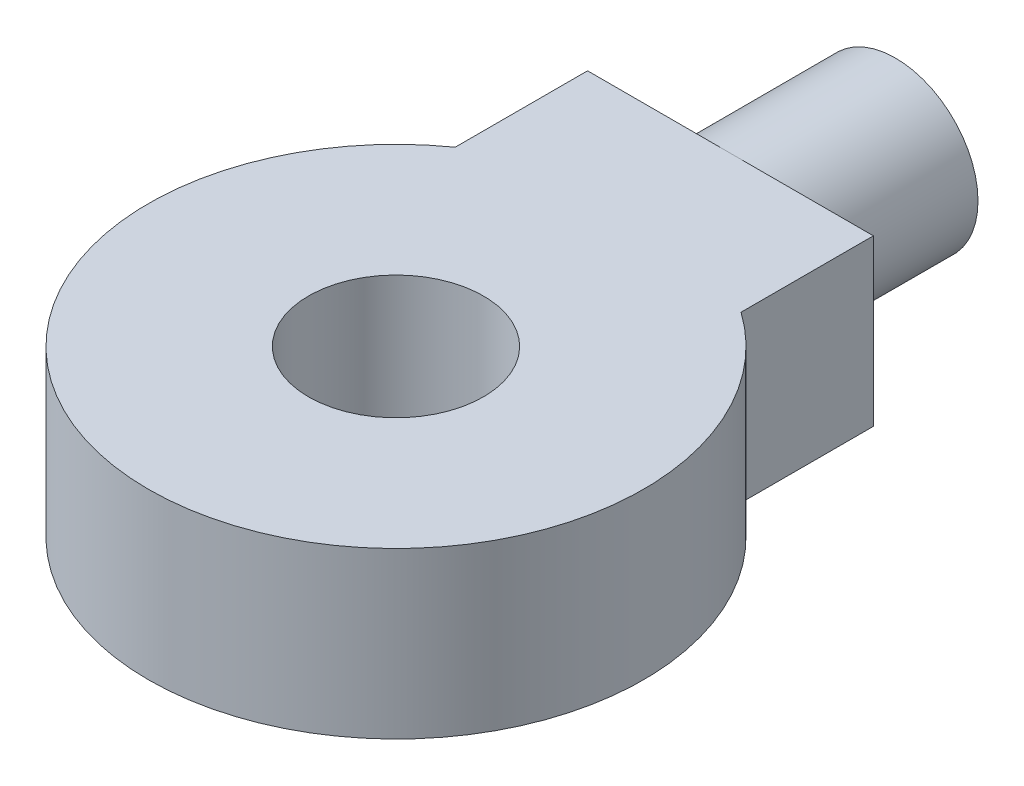
SolidWorks part; units mm, degrees
ref_plane "Front Plane" through (0, 0, 0) normal (0, 0, 1) x (1, 0, 0)
ref_plane "Top Plane" through (0, 0, 0) normal (0, 1, 0) x (1, 0, 0)
ref_plane "Right Plane" through (0, 0, 0) normal (1, 0, 0) x (0, 0, -1)
sketch "Sketch1" plane through (0, 0, 2.5962) normal (0, 0, 1) x (1, 0, 0)
  circle A0 centre (21.0048, 129.3152) radius 2.5
  dimension "D1" = 5
extrude "Boss-Extrude1" add sketch "Sketch1" against normal blind 5
sketch "Sketch2" plane through (0, 0, 2.5962) normal (0, 0, 1) x (1, 0, 0)
  line L1 (16.6747, 131.8152) -> (25.3349, 131.8152)
  line L2 (16.6747, 131.8152) -> (16.6747, 126.8152)
  line L3 (16.6747, 126.8152) -> (25.3349, 126.8152)
  line L4 (25.3349, 131.8152) -> (25.3349, 126.8152)
  line L5 (16.6747, 131.8152) -> (25.3349, 126.8152) construction
  line L6 (16.6747, 126.8152) -> (25.3349, 131.8152) construction
  circle A0 centre (21.0048, 129.3152) radius 2.5 construction
  circle A2 centre (21.0048, 129.3152) radius 5 construction
  point P4 (21.0048, 129.3152)
  dimension "D1" = 5
extrude "Boss-Extrude2" add sketch "Sketch2" along normal blind 11
sketch "Sketch3" plane through (0, 131.8152, 0) normal (0, 1, 0) x (1, 0, 0)
  line L0 (21.0048, -12.7301) -> (21.0048, -13.5962) construction
  line L1 (25.3349, -13.5962) -> (16.6747, -13.5962) construction
  circle A0 centre (21.0048, -12.7301) radius 7.5
  dimension "D1" = 15
extrude "Boss-Extrude3" add sketch "Sketch3" against normal up to surface (5 mm away) up to face at (21.0048, 126.8152, 6.9962)
sketch "Sketch4" plane through (0, 131.8152, 0) normal (0, 1, 0) x (1, 0, 0)
  circle A0 centre (21.0048, -12.7301) radius 2.65
  dimension "D1" = 5.3
extrude "Cut-Extrude1" cut sketch "Sketch4" against normal through all
move or copy body "Body-Move/Copy1" bodies to move or copy 104 copy no translate (-21, -129.32, -12.73)
